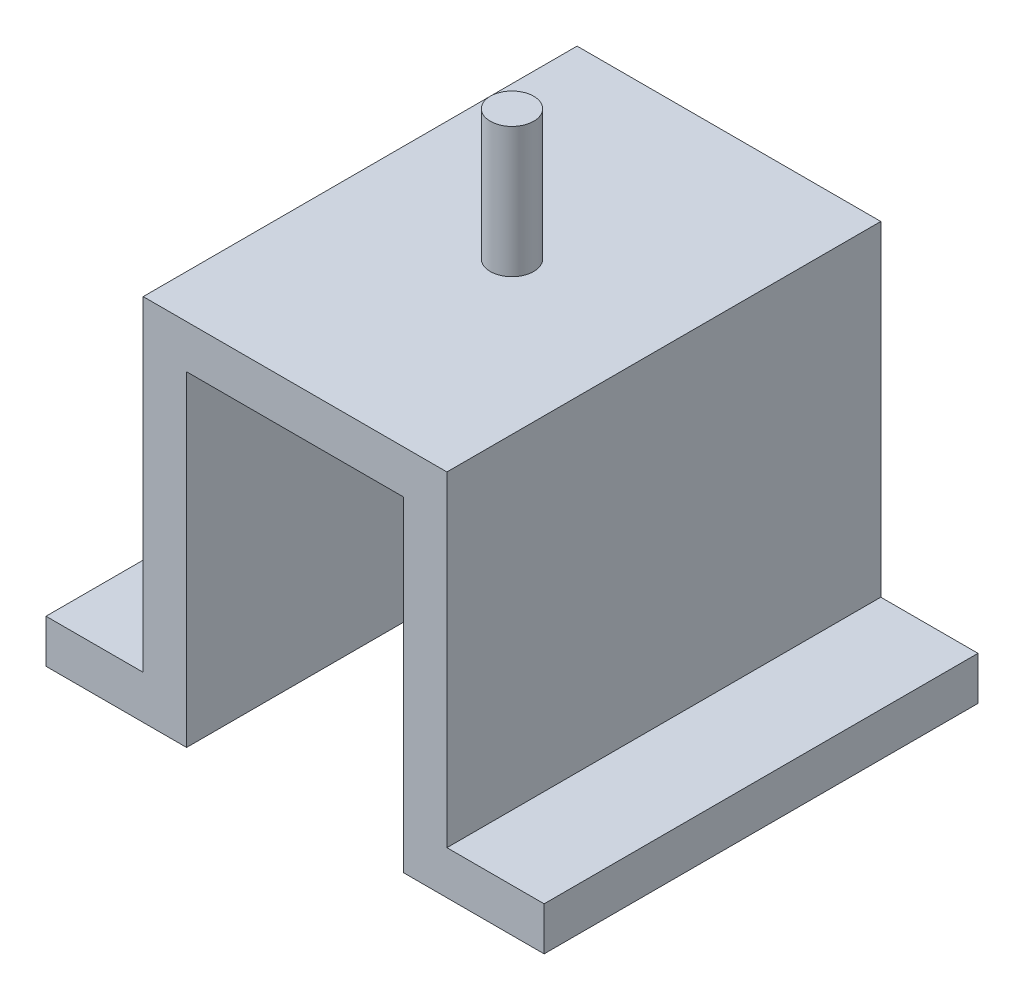
SolidWorks part; units mm, degrees
ref_plane "Front Plane" through (0, 0, 0) normal (0, 0, 1) x (1, 0, 0)
ref_plane "Top Plane" through (0, 0, 0) normal (0, 1, 0) x (1, 0, 0)
ref_plane "Right Plane" through (0, 0, 0) normal (1, 0, 0) x (0, 0, -1)
sketch "Sketch1" plane through (0, 0, 0) normal (0, 0, 1) x (1, 0, 0)
  line L0 (0, 0) -> (0, 22.5728) construction
  line L1 (-57.404, -45.4855) -> (-25, -45.4855)
  line L2 (25, 29.5145) -> (35, 29.5145)
  line L3 (35, 29.5145) -> (35, -35.4855)
  line L4 (35, -35.4855) -> (57.404, -35.4855)
  line L5 (57.404, -35.4855) -> (57.404, -45.4855)
  line L6 (57.404, -45.4855) -> (25, -45.4855)
  line L7 (-57.404, -35.4855) -> (-57.404, -45.4855)
  line L8 (25, 29.5145) -> (25, -45.4855)
  line L9 (-35, -35.4855) -> (-57.404, -35.4855)
  line L10 (-35, 29.5145) -> (-35, -35.4855)
  line L11 (-25, 29.5145) -> (-35, 29.5145)
  line L12 (-25, 29.5145) -> (-25, -45.4855)
  dimension "D1" = 10
  dimension "D2" = 75
  dimension "D3" = 10
  dimension "D4" = 25
extrude "Boss-Extrude1" add sketch "Sketch1" along normal blind 100
sketch "Sketch2" plane through (0, 29.5145, 0) normal (0, 1, 0) x (1, 0, 0)
  line L1 (-35, 0) -> (35, 0)
  line L2 (-35, 0) -> (-35, -100)
  line L3 (-35, -100) -> (35, -100)
  line L4 (35, 0) -> (35, -100)
extrude "Boss-Extrude2" add sketch "Sketch2" along normal blind 10
sketch "Sketch3" plane through (0, 39.5145, 0) normal (0, 1, 0) x (1, 0, 0)
  line L0 (35, 0) -> (-35, 0) construction
  circle A0 centre (0, -50) radius 5
  dimension "D1" = 10
  dimension "D2" = 50
extrude "Boss-Extrude3" add sketch "Sketch3" along normal blind 30
